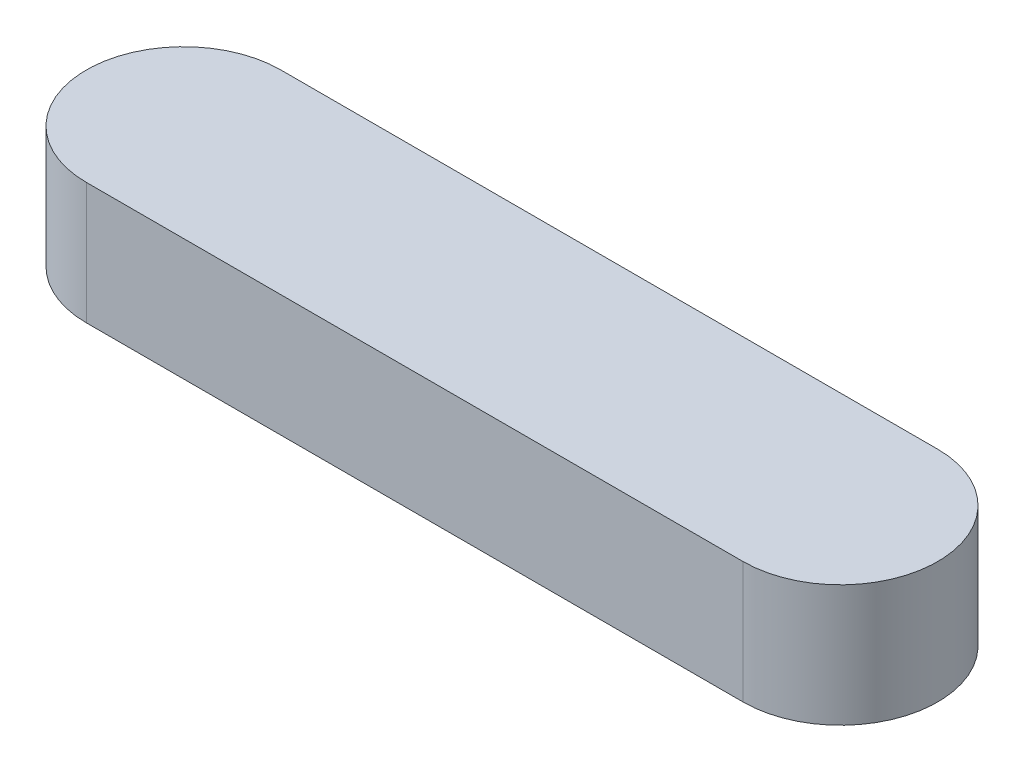
SolidWorks part; units mm, degrees
material "Plain Carbon Steel"
ref_plane "Front" through (0, 0, 0) normal (0, 0, 1) x (1, 0, 0)
ref_plane "Top" through (0, 0, 0) normal (0, 1, 0) x (1, 0, 0)
ref_plane "Right" through (0, 0, 0) normal (1, 0, 0) x (0, 0, -1)
sketch "support-front-body" plane through (0, 0, 0) normal (0, 0, 1) x (1, 0, 0)
  line L0 (-35, 5) -> (35, 5) construction
  line L1 (-35, 10) -> (35, 10)
  line L2 (-35, 10) -> (-35, 0)
  line L3 (-35, 0) -> (35, 0)
  line L4 (35, 10) -> (35, 0)
  line L5 (0, 10) -> (0, 0) construction
  dimension "length" = 70
  dimension "height" = 10
sketch "support-top-body" plane through (0, 0, 0) normal (0, 1, 0) x (1, 0, 0)
  line L0 (-27, 8) -> (27, 8)
  line L1 (27, -8) -> (-27, -8)
  line L2 (35, 0) -> (-35, 0) construction
  line L3 (0, 8) -> (0, -8) construction
  line L4 (-35, 0) -> (35, 0) construction
  arc A0 (27, 8) -> (27, -8) centre (27, 0) cw
  arc A1 (-27, -8) -> (-27, 8) centre (-27, 0) cw
  dimension "width" = 16
ref_plane "ref-plane-top" through (0, 10, 0) normal (0, 1, 0) x (-1, 0, 0)
sketch "Sketch4" plane through (0, 0, 0) normal (0, 1, 0) x (1, 0, 0)
  line L2 (27, 8) -> (-27, 8)
  line L3 (-27, -8) -> (27, -8)
  line L4 (27, 8) -> (-27, 8)
  line L5 (-27, -8) -> (27, -8)
  arc A2 (-27, 8) -> (-27, -8) centre (-27, 0) ccw
  arc A3 (27, -8) -> (27, 8) centre (27, 0) ccw
  arc A4 (-27, 8) -> (-27, -8) centre (-27, 0) ccw
  arc A5 (27, -8) -> (27, 8) centre (27, 0) ccw
  dimension "D1" = 0
extrude "body" add sketch "Sketch4" along normal up to surface (10 mm away) up to plane "ref-plane-top"
